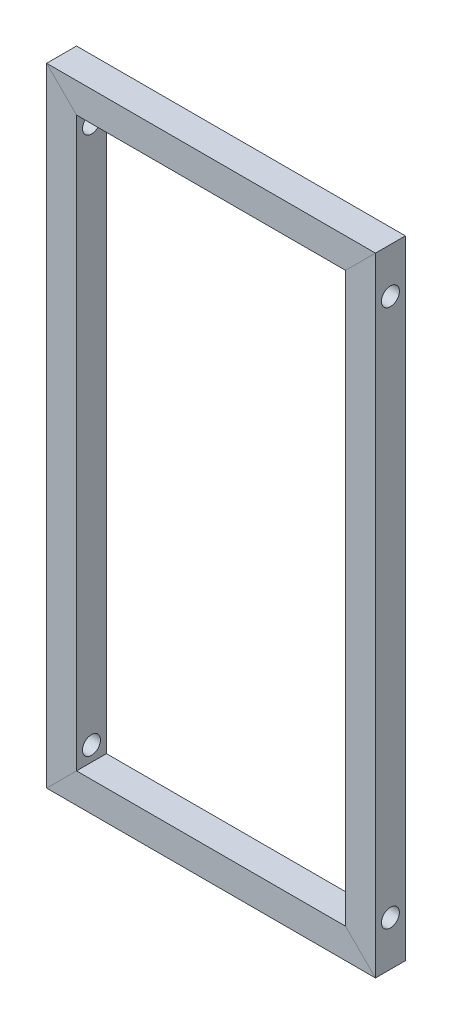
SolidWorks part; units mm, degrees
material "6061-T6 (SS)"
ref_plane "Front Plane" through (0, 0, 0) normal (0, 0, 1) x (1, 0, 0)
ref_plane "Top Plane" through (0, 0, 0) normal (0, 1, 0) x (1, 0, 0)
ref_plane "Right Plane" through (0, 0, 0) normal (1, 0, 0) x (0, 0, -1)
sketch3d "3DSketch1"
  line L0 (0, 0, 0) -> (5.08, 0, 0)
  line L1 (5.08, 0, 0) -> (5.08, -10.16, 0)
  line L2 (5.08, -10.16, 0) -> (0, -10.16, 0)
  line L3 (0, -10.16, 0) -> (0, 0, 0)
  dimension "D1" = 5.08
  dimension "D2" = 10.16
sketch "Sketch1" plane through (0, 0, 0) normal (1, 0, 0) x (0, 0, -1)
  line L1 (-0.254, 0.254) -> (0.254, 0.254)
  line L2 (-0.254, 0.254) -> (-0.254, -0.254)
  line L3 (-0.254, -0.254) -> (0.254, -0.254)
  line L4 (0.254, 0.254) -> (0.254, -0.254)
  line L5 (-0.254, 0.254) -> (0.254, -0.254) construction
  line L6 (-0.254, -0.254) -> (0.254, 0.254) construction
  point P0 (0, 0)
  dimension "D1" = 0.508
  dimension "D2" = 0.508
sweep "Sweep1" add profiles "Sketch1" path "3DSketch1"
sketch "Sketch2" plane through (5.334, 0, 0) normal (1, 0, 0) x (0, 0, -1)
  line L3 (0.254, 0.254) -> (0.254, -10.414) construction
  line L4 (-0.254, 0.254) -> (0.254, 0.254) construction
  circle A0 centre (0, -0.508) radius 0.1524
  point P3 (0, 0)
  point P4 (0, 0)
  point P6 (0, 0)
  dimension "D1" = 0.254
  dimension "D2" = 0.762
  dimension "D3" = 0.3048
extrude "Cut-Extrude1" cut sketch "Sketch2" against normal through all
ref_plane "Plane1" through (0, -5.08, 0) normal (0, 1, 0) x (1, 0, 0)
mirror "Mirror1" about plane through (0, -5.08, 0) normal (0, 1, 0) of "Cut-Extrude1"
